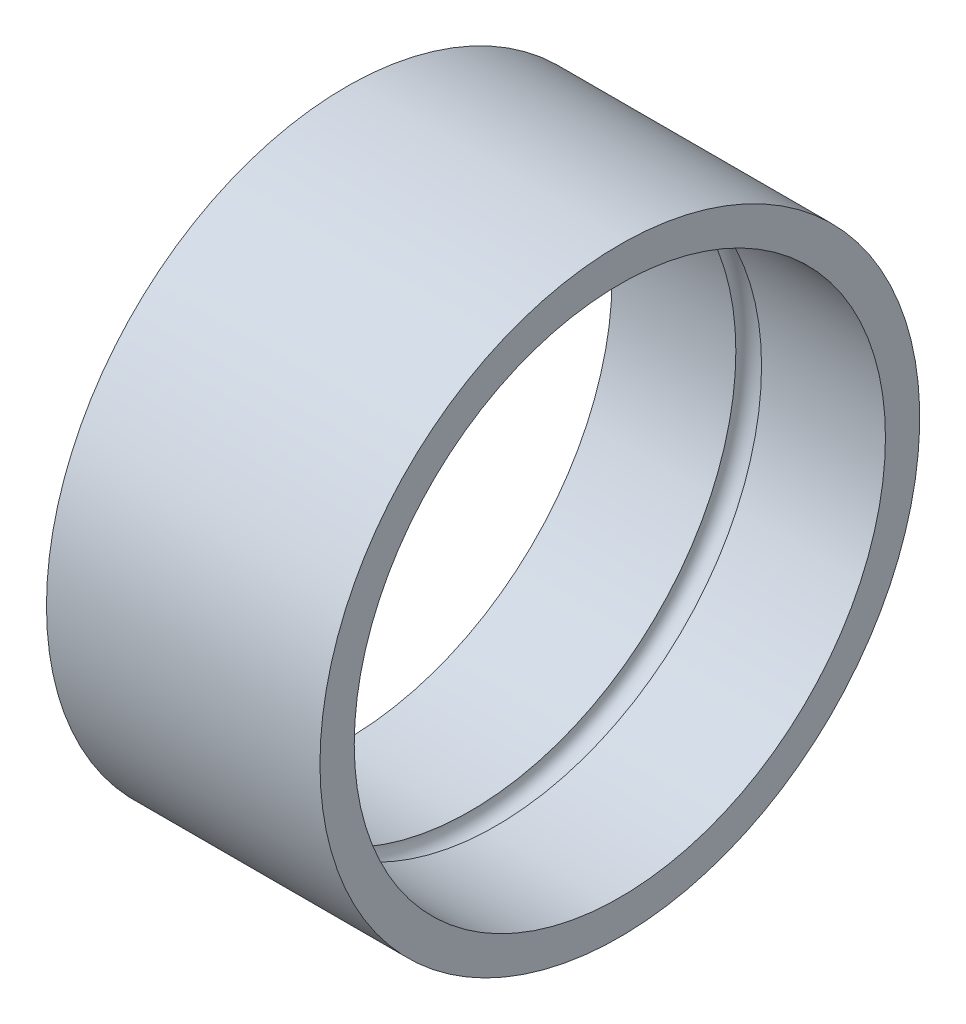
SolidWorks part; units mm, degrees
material "Bronze comercial , UNS C22000 (Bronze 90-10)"
ref_plane "Plano frontal" through (0, 0, 0) normal (0, 0, 1) x (1, 0, 0)
ref_plane "Plano superior" through (0, 0, 0) normal (0, 1, 0) x (1, 0, 0)
ref_plane "Plano direito" through (0, 0, 0) normal (1, 0, 0) x (0, 0, -1)
sketch "Esboço1" plane through (0, 0, 0) normal (0, 0, 1) x (1, 0, 0)
  line L0 (-7.98, 0) -> (7.98, 0) construction
  line L1 (0.75, 15.5) -> (7.98, 15.5)
  line L2 (-7.98, 17.5) -> (7.98, 17.5)
  line L3 (-7.98, 17.5) -> (-7.98, 15.5)
  line L4 (-7.98, 15.5) -> (-0.75, 15.5)
  line L5 (7.98, 17.5) -> (7.98, 15.5)
  arc A0 (0.75, 15.5) -> (-0.75, 15.5) centre (0, 15.5) ccw
  point P9 (0, 0)
  point P11 (0, 0)
  dimension "D4" = 0.75
  dimension "D1" = 35
  dimension "D2" = 31
  dimension "D3" = 15.96
revolve "Revolução1" add sketch "Esboço1" angle 360 about L0
